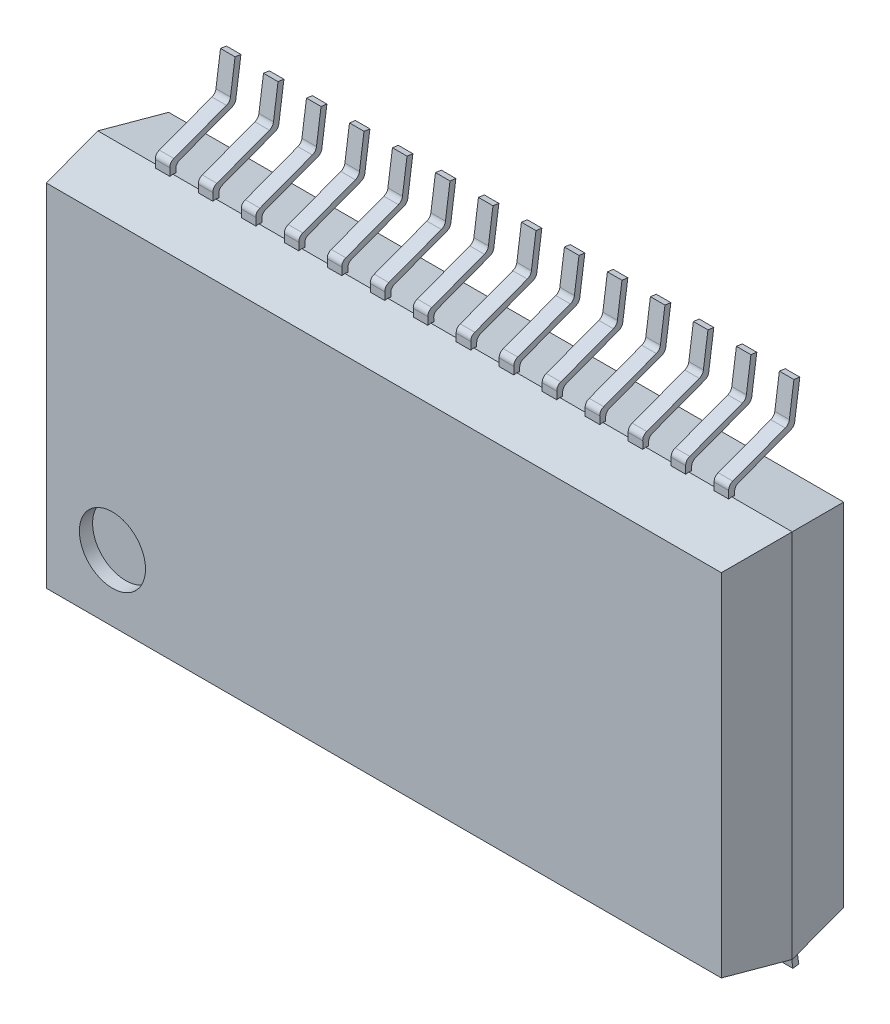
SolidWorks part; units mm, degrees
ref_plane "Plano frontal" through (0, 0, 0) normal (0, 0, 1) x (1, 0, 0)
ref_plane "Plano superior" through (0, 0, 0) normal (0, 1, 0) x (1, 0, 0)
ref_plane "Plano direito" through (0, 0, 0) normal (1, 0, 0) x (0, 0, -1)
sketch "Esboço1" plane through (0, 0, 0) normal (0, 0, 1) x (1, 0, 0)
  line L1 (-0.915, 5.6) -> (9.585, 5.6)
  line L2 (-0.915, 5.6) -> (-0.915, 0)
  line L3 (-0.915, 0) -> (9.585, 0)
  line L4 (9.585, 5.6) -> (9.585, 0)
extrude "Extrusão1" add sketch "Esboço1" along normal blind 0.925 draft 9
sketch "Esboço2" plane through (0, 0, 0) normal (0, 0, 1) x (1, 0, 0)
  line L0 (-0.915, 5.6) -> (9.585, 5.6)
  line L1 (-0.915, 5.6) -> (-0.915, 0)
  line L2 (-0.915, 0) -> (9.585, 0)
  line L3 (9.585, 5.6) -> (9.585, 0)
extrude "Extrusão2" add sketch "Esboço2" against normal blind 0.925 draft 9 separate body
sketch "Esboço3" plane through (0, 0, 0) normal (1, 0, 0) x (0, 0, -1)
  line L2 (1.0297, 6.6538) -> (0.9405, 6.6663)
  line L4 (-0.045, 5.7058) -> (-0.045, 5.5929)
  line L5 (1.0297, 6.6538) -> (0.9524, 6.1038)
  line L6 (0.0161, 5.7974) -> (0.8101, 6.0963)
  line L7 (0.8715, 6.1752) -> (0.9405, 6.6663)
  line L8 (0.045, 5.6435) -> (0.045, 5.5929)
  line L9 (0, 0) -> (0.045, 0.0071)
  line L10 (0.1061, 5.7351) -> (0.8949, 6.0321)
  line L11 (-0.925, 5.4535) -> (0, 5.6) construction
  line L12 (0.925, 5.4535) -> (0, 5.6) construction
  line L13 (-0.045, 5.5929) -> (0, 5.6)
  line L14 (0, 5.6) -> (0.045, 5.5929)
  line L15 (-0.045, 0.0071) -> (0, 0)
  line L16 (0.0909, -0.106) -> (0.8798, -0.403)
  line L17 (0.045, -0.072) -> (0.045, 0.0071)
  line L18 (0.8564, -0.5461) -> (0.9254, -1.0372)
  line L19 (0.0009, -0.1683) -> (0.7949, -0.4672)
  line L20 (1.0145, -1.0247) -> (0.9372, -0.4747)
  line L21 (-0.045, -0.1343) -> (-0.045, 0.0071)
  line L22 (1.0145, -1.0247) -> (0.9254, -1.0372)
  arc A0 (-0.045, 5.7058) -> (0.0161, 5.7974) centre (0.0425, 5.7136) cw
  arc A1 (0.045, 5.6435) -> (0.1061, 5.7351) centre (0.1325, 5.6513) cw
  arc A2 (0.8949, 6.0321) -> (0.9524, 6.1038) centre (0.861, 6.1181) ccw
  arc A3 (0.8715, 6.1752) -> (0.8101, 6.0963) centre (0.7793, 6.1836) cw
  arc A4 (0.8564, -0.5461) -> (0.7949, -0.4672) centre (0.7642, -0.5545) ccw
  arc A5 (0.8798, -0.403) -> (0.9372, -0.4747) centre (0.8459, -0.489) cw
  arc A6 (0.045, -0.072) -> (0.0909, -0.106) centre (0.1174, -0.0222) ccw
  arc A7 (-0.045, -0.1343) -> (0.0009, -0.1683) centre (0.0274, -0.0845) ccw
extrude "Extrusão3" add sketch "Esboço3" along normal blind 0.22 separate body
pattern_linear "Padrão linear2" count 14 spacing 0.65 along (1, 0, 0) of bodies 104 103
sketch "Esboço7" plane through (0, 0, 0) normal (0, 0, 1) x (1, 0, 0)
  circle A1 centre (0.2315, 1.1465) radius 0.5
extrude "Corte-extrusão1" cut sketch "Esboço7" along normal blind 0.2 and the other way blind 0.2 from surface at 0.925 starting at face at (4.335, 2.8, 0.925)
